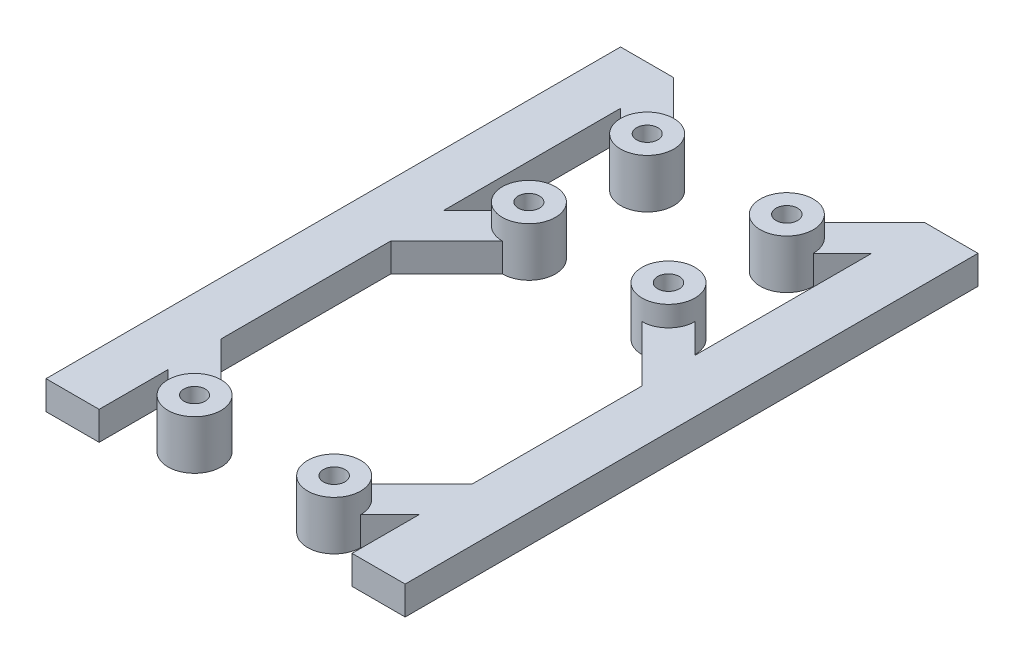
SolidWorks part; units mm, degrees
material "ABS PC"
ref_plane "Front Plane" through (0, 0, 0) normal (0, 0, 1) x (1, 0, 0)
ref_plane "Top Plane" through (0, 0, 0) normal (0, 1, 0) x (1, 0, 0)
ref_plane "Right Plane" through (0, 0, 0) normal (1, 0, 0) x (0, 0, -1)
sketch "Sketch1" plane through (0, 72.1567, 0) normal (0, -1, 0) x (-1, 0, 0)
  circle A0 centre (-13.4344, 13.8799) radius 1.6764
  circle A1 centre (-13.4344, 13.8799) radius 4.1275
  circle A2 centre (38.5848, 13.8799) radius 1.6764
  circle A3 centre (38.5848, 13.8799) radius 4.1275
  circle A4 centre (-13.4344, -38.0885) radius 1.6764
  circle A5 centre (-13.4344, -38.0885) radius 4.1275
  circle A6 centre (38.5848, -38.0885) radius 1.6764
  circle A7 centre (38.5848, -38.0885) radius 4.1275
  circle A8 centre (-13.4344, -56.4781) radius 1.6764
  circle A9 centre (-13.4344, -56.4781) radius 4.1275
  circle A10 centre (38.5848, -56.4781) radius 1.6764
  circle A11 centre (38.5848, -56.4781) radius 4.1275
  circle A12 centre (-13.4344, -108.4465) radius 1.6764
  circle A13 centre (-13.4344, -108.4465) radius 4.1275
  circle A14 centre (38.5848, -108.4465) radius 1.6764
  circle A15 centre (38.5848, -108.4465) radius 4.1275
  circle A16 centre (-13.4344, -126.8361) radius 1.6764
  circle A17 centre (-13.4344, -126.8361) radius 4.1275
  circle A18 centre (38.5848, -126.8361) radius 1.6764
  circle A19 centre (38.5848, -126.8361) radius 4.1275
  circle A20 centre (-13.4344, -178.8045) radius 1.6764
  circle A21 centre (-13.4344, -178.8045) radius 4.1275
  circle A22 centre (38.5848, -178.8045) radius 1.6764
  circle A23 centre (38.5848, -178.8045) radius 4.1275
  dimension "D1" = 8.255
  dimension "D2" = 8.255
  dimension "D3" = 8.255
  dimension "D4" = 8.255
  dimension "D5" = 8.255
  dimension "D7" = 8.255
  dimension "D8" = 8.255
  dimension "D9" = 8.255
  dimension "D10" = 8.255
  dimension "D11" = 8.255
  dimension "D12" = 8.255
extrude "Boss-Extrude1" add sketch "Sketch1" along normal blind 3.175
sketch "Sketch2" plane through (0, 68.9817, 0) normal (0, -1, 0) x (-1, 0, 0)
  line L0 (34.4573, -178.8045) -> (12.5752, -156.9456)
  line L1 (-4.7634, -166.0153) -> (-4.7634, -139.6253)
  line L2 (-9.3069, -126.8361) -> (-4.7634, -131.3747)
  line L3 (38.5848, -130.9636) -> (29.9139, -139.6253)
  line L4 (-13.4344, -174.677) -> (-4.7634, -166.0153)
  line L5 (38.5848, -104.319) -> (29.9139, -95.6573)
  line L6 (-13.4344, -60.6056) -> (-4.7634, -69.2673)
  line L7 (-13.4344, -104.319) -> (-4.7634, -95.6573)
  line L8 (-9.3069, -108.4465) -> (-4.7634, -103.9079)
  line L9 (34.4573, -38.0885) -> (29.9139, -33.5499)
  line L10 (38.5848, -33.961) -> (29.9139, -25.2993)
  line L11 (38.5848, 9.7524) -> (29.9139, 1.0907)
  line L12 (-13.4344, -33.961) -> (8.4456, -12.1043)
  line L13 (-4.7634, 1.0907) -> (-13.4344, 9.7524)
  line L14 (3.4959, -7.1599) -> (3.4959, -17.0487)
  line L15 (3.4959, -157.7647) -> (8.4456, -152.8203)
  line L16 (29.9139, -166.0153) -> (38.5848, -174.677)
  line L17 (29.9139, -166.0153) -> (29.9139, -139.6253)
  line L18 (3.4959, -25.2993) -> (3.4959, -69.2673)
  line L19 (21.6546, -7.1599) -> (21.6546, -17.0487)
  line L20 (21.6546, -147.8759) -> (16.7049, -152.8203)
  line L21 (29.9139, -131.3747) -> (34.4573, -126.8361)
  line L22 (29.9139, -131.3747) -> (29.9139, -103.9079)
  line L23 (21.6546, -147.8759) -> (21.6546, -157.7647)
  line L24 (16.7049, -152.8203) -> (21.6546, -157.7647)
  line L25 (12.5752, -156.9456) -> (-9.3069, -178.8045)
  line L26 (12.5752, -148.695) -> (21.6546, -139.6253)
  line L27 (8.4456, -152.8203) -> (3.4959, -147.8759)
  line L28 (-4.7634, -139.6253) -> (-13.4344, -130.9636)
  line L29 (3.4959, -147.8759) -> (3.4959, -157.7647)
  line L30 (3.4959, -139.6253) -> (12.5752, -148.695)
  line L31 (-4.7634, -131.3747) -> (-4.7634, -103.9079)
  line L33 (-4.7634, -95.6573) -> (-4.7634, -69.2673)
  line L35 (3.4959, -95.6573) -> (3.4959, -139.6253)
  line L40 (29.9139, -103.9079) -> (34.4573, -108.4465)
  line L41 (21.6546, -95.6573) -> (21.6546, -139.6253)
  line L43 (29.9139, -95.6573) -> (29.9139, -69.2673)
  line L44 (29.9139, -69.2673) -> (38.5848, -60.6056)
  line L45 (21.6546, -77.5179) -> (21.6546, -87.4067)
  line L46 (29.9139, -61.0167) -> (34.4573, -56.4781)
  line L47 (29.9139, -61.0167) -> (29.9139, -33.5499)
  line L48 (3.4959, -77.5179) -> (3.4959, -87.4067)
  line L50 (-4.7634, -61.0167) -> (-4.7634, -33.5499)
  line L51 (-4.7634, -61.0167) -> (-9.3069, -56.4781)
  line L52 (29.9139, -25.2993) -> (29.9139, 1.0907)
  line L53 (21.6546, -25.2993) -> (12.5752, -16.2296)
  line L54 (21.6546, -25.2993) -> (21.6546, -69.2673)
  line L55 (21.6546, -17.0487) -> (16.7049, -12.1043)
  line L56 (12.5752, -16.2296) -> (3.4959, -25.2993)
  line L57 (12.5752, -7.979) -> (34.4573, 13.8799)
  line L58 (8.4456, -12.1043) -> (3.4959, -7.1599)
  line L59 (12.5752, -7.979) -> (-9.3069, 13.8799)
  line L60 (21.6546, -7.1599) -> (16.7049, -12.1043)
  line L61 (-4.7634, -33.5499) -> (-9.3069, -38.0885)
  line L62 (-4.7634, -25.2993) -> (-4.7634, 1.0907)
  line L63 (3.4959, -87.4067) -> (3.4959, -95.6573)
  line L64 (21.6546, -95.6573) -> (21.6546, -87.4067)
  line L65 (21.6546, -77.5179) -> (21.6546, -69.2673)
  line L66 (3.4959, -77.5179) -> (3.4959, -69.2673)
  circle A0 centre (-13.4344, 13.8799) radius 1.6764
  arc A1 (-9.3069, 13.8799) -> (-13.4344, 9.7524) centre (-13.4344, 13.8799) ccw
  circle A2 centre (38.5848, 13.8799) radius 1.6764
  arc A3 (38.5848, 9.7524) -> (34.4573, 13.8799) centre (38.5848, 13.8799) ccw
  circle A4 centre (38.5848, -38.0885) radius 1.6764
  arc A5 (34.4573, -38.0885) -> (38.5848, -33.961) centre (38.5848, -38.0885) ccw
  circle A6 centre (-13.4344, -38.0885) radius 1.6764
  arc A7 (-13.4344, -33.961) -> (-9.3069, -38.0885) centre (-13.4344, -38.0885) ccw
  circle A8 centre (-13.4344, -56.4781) radius 1.6764
  arc A9 (-9.3069, -56.4781) -> (-13.4344, -60.6056) centre (-13.4344, -56.4781) ccw
  circle A10 centre (38.5848, -56.4781) radius 1.6764
  arc A11 (38.5848, -60.6056) -> (34.4573, -56.4781) centre (38.5848, -56.4781) ccw
  circle A12 centre (-13.4344, -108.4465) radius 1.5974
  arc A13 (-13.4344, -104.319) -> (-9.3069, -108.4465) centre (-13.4344, -108.4465) ccw
  circle A14 centre (38.5848, -108.4465) radius 1.6764
  arc A15 (34.4573, -108.4465) -> (38.5848, -104.319) centre (38.5848, -108.4465) ccw
  circle A16 centre (-13.4344, -126.8361) radius 1.6764
  arc A17 (-9.3069, -126.8361) -> (-13.4344, -130.9636) centre (-13.4344, -126.8361) ccw
  circle A18 centre (38.5848, -126.8361) radius 1.6764
  arc A19 (38.5848, -130.9636) -> (34.4573, -126.8361) centre (38.5848, -126.8361) ccw
  circle A20 centre (-13.4344, -178.8045) radius 1.6764
  arc A21 (-13.4344, -174.677) -> (-9.3069, -178.8045) centre (-13.4344, -178.8045) ccw
  circle A22 centre (38.5848, -178.8045) radius 1.6764
  arc A23 (34.4573, -178.8045) -> (38.5848, -174.677) centre (38.5848, -178.8045) ccw
extrude "Boss-Extrude2" add sketch "Sketch2" along normal blind 4.445
sketch "Sketch3" plane through (0, 68.9817, 0) normal (0, -1, 0) x (-1, 0, 0)
  circle A0 centre (-13.4344, 13.8799) radius 1.6764
  circle A1 centre (-13.4344, 13.8799) radius 4.1275
extrude "Boss-Extrude3" add sketch "Sketch3" along normal blind 6.35
sketch "Sketch5" plane through (0, 72.1567, 0) normal (0, 1, 0) x (1, 0, 0)
  line L0 (40.5166, -25.2993) -> (40.5166, 26.718)
  line L1 (40.5166, -25.2993) -> (-53.4105, -25.2993)
  line L3 (40.5166, 26.718) -> (-53.4105, 26.718)
  line L4 (-53.4105, -25.2993) -> (-53.4105, 26.718)
extrude "Cut-Extrude1" cut sketch "Sketch5" against normal through all
sketch "Sketch6" plane through (0, 72.1567, 0) normal (0, 1, 0) x (1, 0, 0)
  line L0 (35.7165, -114.3401) -> (35.7165, -189.203)
  line L1 (-63.7962, -114.3401) -> (35.7165, -114.3401)
  line L3 (35.7165, -189.203) -> (-63.7962, -189.203)
  line L4 (-63.7962, -114.3401) -> (-63.7962, -189.203)
extrude "Cut-Extrude3" cut sketch "Sketch6" against normal through all
sketch "Sketch7" plane through (0, 72.1567, 0) normal (0, 1, 0) x (1, 0, 0)
  line L0 (-21.6546, -114.3401) -> (-21.6546, -25.2993) construction
  line L1 (-77.2171, -114.3401) -> (-77.2171, -25.2993) construction
  line L3 (-21.6546, -25.2993) -> (-29.9139, -25.2993) construction
  line L4 (-21.6546, -25.2993) -> (-21.6546, -114.3401) construction
  line L5 (-77.2171, -114.6067) -> (-77.2171, -25.2993)
  line L19 (-77.2171, -114.6067) -> (-68.9577, -114.6067)
  line L20 (-68.9577, -114.6067) -> (-68.9577, -103.9079)
  line L21 (-68.9577, -103.9079) -> (-64.4143, -108.4465)
  line L22 (-60.2868, -104.319) -> (-68.9577, -95.6573)
  line L23 (-68.9577, -95.6573) -> (-68.9577, -69.2673)
  line L24 (-68.9577, -69.2673) -> (-60.2868, -60.6056)
  line L25 (-64.4143, -56.4781) -> (-68.9577, -61.0167)
  line L26 (-68.9577, -61.0167) -> (-68.9577, -33.5499)
  line L27 (-68.9577, -33.5499) -> (-64.4143, -38.0885)
  line L28 (-60.2868, -33.961) -> (-68.9577, -25.2993)
  line L29 (-68.9577, -25.2993) -> (-77.2171, -25.2993)
  arc A9 (-60.2868, -104.319) -> (-64.4143, -108.4465) centre (-60.2868, -108.4465) ccw
  arc A10 (-64.4143, -56.4781) -> (-60.2868, -60.6056) centre (-60.2868, -56.4781) ccw
  arc A11 (-60.2868, -33.961) -> (-64.4143, -38.0885) centre (-60.2868, -38.0885) ccw
  circle A12 centre (-60.2868, -38.0885) radius 4.1275
  circle A13 centre (-60.2868, -56.4781) radius 4.1275
  circle A14 centre (-60.2868, -108.4465) radius 4.1275
  circle A16 centre (-60.2868, -38.0885) radius 1.651
  circle A17 centre (-60.2868, -56.4781) radius 1.651
  circle A18 centre (-60.2868, -108.4465) radius 1.651
  dimension "D2" = 3.302
  dimension "D3" = 3.302
  dimension "D4" = 3.302
  dimension "D1" = 55.5625
extrude "Boss-Extrude5" add sketch "Sketch7" against normal up to surface (7.62 mm away) separate body contours A11 A12 A16 | A10 A13 A17 | A9 A14 A18 up to face at (-32.452, 64.5367, 69.9706)
sketch "Sketch9" plane through (0, 68.9817, 0) normal (0, 1, 0) x (1, 0, 0)
  line L0 (-68.9577, -25.2993) -> (-77.2171, -25.2993) construction
  line L1 (-60.2868, -33.961) -> (-68.9577, -25.2993) construction
  line L2 (-68.9577, -33.5499) -> (-64.4143, -38.0885) construction
  line L3 (-64.4143, -56.4781) -> (-68.9577, -61.0167) construction
  line L4 (-68.9577, -61.0167) -> (-68.9577, -33.5499) construction
  line L5 (-77.2171, -114.6067) -> (-77.2171, -25.2993) construction
  line L6 (-68.9577, -95.6573) -> (-68.9577, -69.2673) construction
  line L7 (-68.9577, -69.2673) -> (-60.2868, -60.6056) construction
  line L8 (-60.2868, -104.319) -> (-68.9577, -95.6573) construction
  line L9 (-68.9577, -103.9079) -> (-64.4143, -108.4465) construction
  line L10 (-68.9577, -114.6067) -> (-68.9577, -103.9079) construction
  line L11 (-77.2171, -114.6067) -> (-68.9577, -114.6067) construction
  line L36 (-68.9577, -25.2993) -> (-77.2171, -25.2993)
  line L37 (-60.2868, -33.961) -> (-68.9577, -25.2993)
  line L38 (-68.9577, -33.5499) -> (-64.4143, -38.0885)
  line L39 (-64.4143, -56.4781) -> (-68.9577, -61.0167)
  line L40 (-68.9577, -61.0167) -> (-68.9577, -33.5499)
  line L41 (-77.2171, -114.6067) -> (-77.2171, -25.2993)
  line L42 (-68.9577, -95.6573) -> (-68.9577, -69.2673)
  line L43 (-68.9577, -69.2673) -> (-60.2868, -60.6056)
  line L44 (-60.2868, -104.319) -> (-68.9577, -95.6573)
  line L45 (-68.9577, -103.9079) -> (-64.4143, -108.4465)
  line L46 (-68.9577, -114.6067) -> (-68.9577, -103.9079)
  line L47 (-77.2171, -114.6067) -> (-68.9577, -114.6067)
  arc A0 (-60.2868, -33.961) -> (-64.4143, -38.0885) centre (-60.2868, -38.0885) ccw construction
  arc A1 (-64.4143, -56.4781) -> (-60.2868, -60.6056) centre (-60.2868, -56.4781) ccw construction
  arc A2 (-60.2868, -33.961) -> (-64.4143, -38.0885) centre (-60.2868, -38.0885) ccw
  arc A3 (-60.2868, -104.319) -> (-64.4143, -108.4465) centre (-60.2868, -108.4465) ccw construction
  arc A4 (-60.2868, -104.319) -> (-64.4143, -108.4465) centre (-60.2868, -108.4465) ccw
  arc A9 (-64.4143, -56.4781) -> (-60.2868, -60.6056) centre (-60.2868, -56.4781) ccw
extrude "Boss-Extrude6" add sketch "Sketch9" against normal up to surface (4.445 mm away) up to face at (-32.452, 64.5367, 69.9706)
sketch "Sketch10" plane through (0, 72.1567, 0) normal (0, 1, 0) x (1, 0, 0)
  line L1 (44.9342, -120.5329) -> (-8.2864, -120.5329)
  line L2 (44.9342, -120.5329) -> (44.9342, -22.0619)
  line L3 (44.9342, -22.0619) -> (-8.2864, -22.0619)
  line L4 (-8.2864, -120.5329) -> (-8.2864, -22.0619)
extrude "Cut-Extrude4" cut sketch "Sketch10" against normal through all
